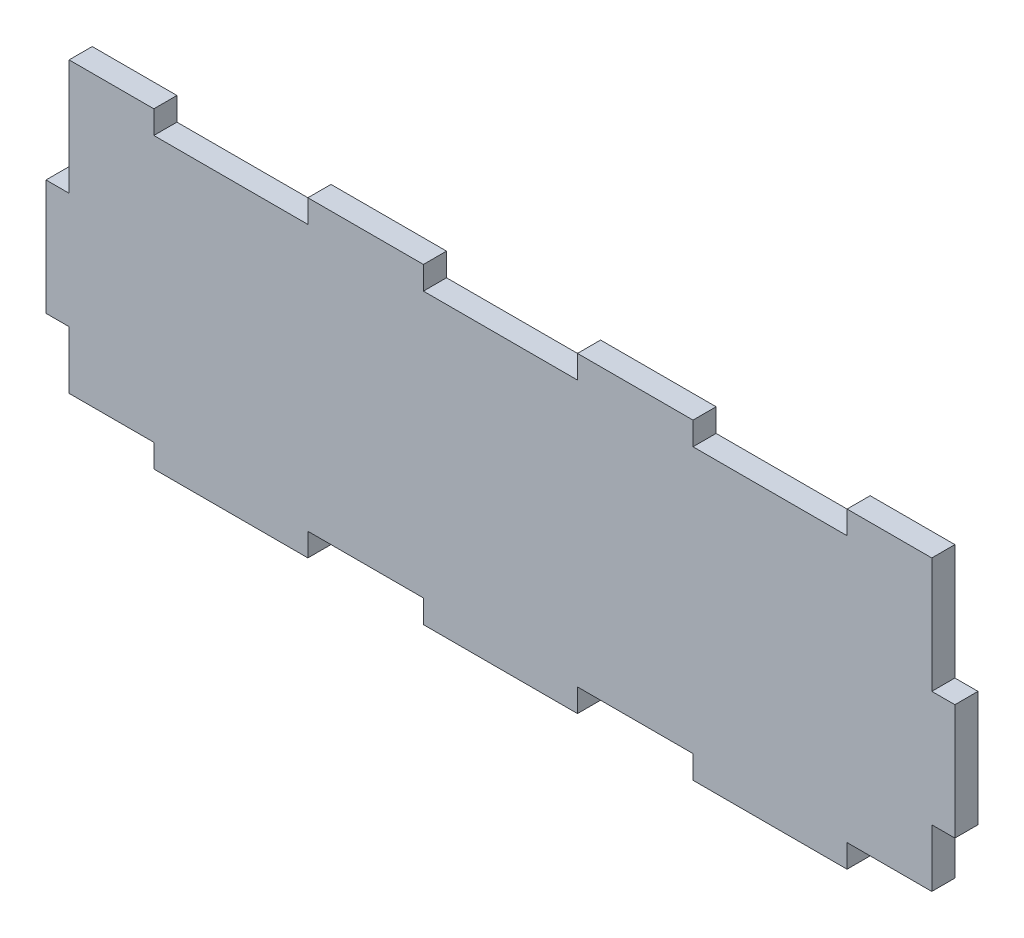
SolidWorks part; units mm, degrees
ref_plane "Front Plane" through (0, 0, 0) normal (0, 0, 1) x (1, 0, 0)
ref_plane "Top Plane" through (0, 0, 0) normal (0, 1, 0) x (1, 0, 0)
ref_plane "Right Plane" through (0, 0, 0) normal (1, 0, 0) x (0, 0, -1)
sketch "Sketch2" plane through (0, 0, 0) normal (0, 0, 1) x (1, 0, 0)
  line L0 (0, -55) -> (0, 55) construction
  line L1 (56, -30) -> (-56, -30)
  line L2 (56, -30) -> (56, 30)
  line L3 (56, 30) -> (-56, 30)
  line L4 (-56, -30) -> (-56, 30)
  line L5 (56, -30) -> (-56, 30) construction
  line L6 (56, 30) -> (-56, -30) construction
  line L7 (-10, -33) -> (10, -33)
  line L8 (-10, -33) -> (-10, -30)
  line L9 (-10, -30) -> (10, -30)
  line L10 (10, -33) -> (10, -30)
  line L11 (-10, -33) -> (10, -30) construction
  line L12 (-10, -30) -> (10, -33) construction
  line L13 (25, -33) -> (45, -33)
  line L14 (25, -33) -> (25, -30)
  line L15 (25, -30) -> (45, -30)
  line L16 (45, -33) -> (45, -30)
  line L17 (25, -33) -> (45, -30) construction
  line L18 (25, -30) -> (45, -33) construction
  line L19 (59, 7.5) -> (56, 7.5)
  line L20 (59, 7.5) -> (59, 22.5)
  line L21 (59, 22.5) -> (56, 22.5)
  line L22 (56, 7.5) -> (56, 22.5)
  line L23 (59, 7.5) -> (56, 22.5) construction
  line L24 (59, 22.5) -> (56, 7.5) construction
  line L25 (59, -22.5) -> (56, -22.5)
  line L26 (59, -22.5) -> (59, -7.5)
  line L27 (59, -7.5) -> (56, -7.5)
  line L28 (56, -22.5) -> (56, -7.5)
  line L29 (59, -22.5) -> (56, -7.5) construction
  line L30 (59, -7.5) -> (56, -22.5) construction
  line L31 (-59, 22.5) -> (-56, 22.5)
  line L32 (-56, 7.5) -> (-56, 22.5)
  line L33 (-59, 7.5) -> (-56, 7.5)
  line L34 (-59, 7.5) -> (-59, 22.5)
  line L35 (-59, -7.5) -> (-56, -7.5)
  line L36 (-56, -22.5) -> (-56, -7.5)
  line L37 (-59, -22.5) -> (-56, -22.5)
  line L38 (-59, -22.5) -> (-59, -7.5)
  line L39 (-25, -30) -> (-45, -30)
  line L40 (-45, -33) -> (-45, -30)
  line L41 (-25, -33) -> (-45, -33)
  line L42 (-25, -33) -> (-25, -30)
  line L43 (-10, -33) -> (-10, -30)
  line L44 (10, -33) -> (10, -30)
  line L46 (-56, -30) -> (56, -30)
  line L47 (-56, -30) -> (-56, 7.5)
  line L48 (-56, 7.5) -> (56, 7.5)
  line L49 (56, -30) -> (56, 7.5)
  point P0 (0, 0)
  point P6 (0, -31.5)
  point P11 (35, -31.5)
  point P16 (57.5, -15)
  point P17 (57.5, 15)
  dimension "D1" = 112
  dimension "D2" = 60
  dimension "D3" = 3
  dimension "D4" = 20
  dimension "D5" = 15
  dimension "D6" = 15
  dimension "D7" = 3
  dimension "D8" = 7.5
  dimension "D9" = 15
extrude "Boss-Extrude1" add sketch "Sketch2" along normal blind 3 contours L4 L1 L2 L3 | L41 L42 L1 L40 | L7 L10 L1 L8 | L13 L16 L1 L14 | L26 L27 L28 L25 | L35 L36 L37 L38 | L31 L32 L33 L34 | L20 L19 L22 L21
sketch "Sketch4" plane through (0, 0, 3) normal (0, 0, 1) x (1, 0, 0)
  line L0 (59, 7.5) -> (59, 22.5) construction
  line L1 (-59, 7.5) -> (59, 7.5)
  line L2 (-59, 7.5) -> (-59, 30)
  line L3 (-59, 30) -> (59, 30)
  line L4 (59, 7.5) -> (59, 30)
  line L5 (56, 30) -> (-56, 30) construction
  line L6 (0, -1.65) -> (0, 1.65) construction
  line L7 (-10, 4.5) -> (10, 4.5)
  line L8 (-10, 4.5) -> (-10, 7.5)
  line L9 (-10, 7.5) -> (10, 7.5)
  line L10 (10, 4.5) -> (10, 7.5)
  line L11 (-10, 4.5) -> (10, 7.5) construction
  line L12 (-10, 7.5) -> (10, 4.5) construction
  line L13 (-45, 4.5) -> (-25, 4.5)
  line L14 (-45, 4.5) -> (-45, 7.5)
  line L15 (-45, 7.5) -> (-25, 7.5)
  line L16 (-25, 4.5) -> (-25, 7.5)
  line L17 (-45, 4.5) -> (-25, 7.5) construction
  line L18 (-45, 7.5) -> (-25, 4.5) construction
  line L19 (45, 7.5) -> (25, 7.5)
  line L20 (25, 4.5) -> (25, 7.5)
  line L21 (45, 4.5) -> (25, 4.5)
  line L22 (45, 4.5) -> (45, 7.5)
  point P9 (0, 6)
  point P14 (-35, 6)
  line M15 (56, 7.5) -> (59, 7.5)
  line M16 (59, 7.5) -> (59, 22.5)
  line M17 (59, 22.5) -> (56, 22.5)
  line M18 (56, 22.5) -> (56, 30)
  line M19 (56, 30) -> (-56, 30)
  line M20 (-56, 30) -> (-56, 22.5)
  line M21 (-56, 22.5) -> (-59, 22.5)
  line M22 (-59, 22.5) -> (-59, 7.5)
  line M23 (-59, 7.5) -> (-56, 7.5)
  dimension "D1" = 3
  dimension "D2" = 20
  dimension "D3" = 15
extrude "Cut-Extrude2" cut sketch "Sketch4" against normal blind 10 contours L13 L16 L1 L14 | L7 L10 L1 L8 | L21 L22 L1 L20 | L1 M23 M15 M16 M17 M18 M19 M20 M21 M22
